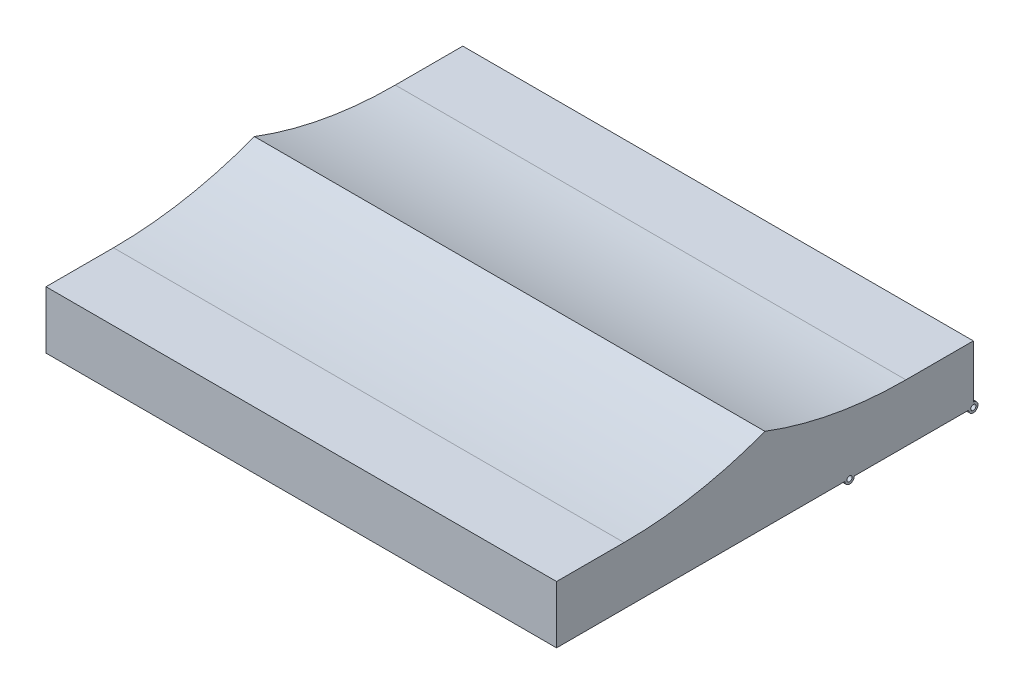
SolidWorks part; units mm, degrees
ref_plane "Plano frontal" through (0, 0, 0) normal (0, 0, 1) x (1, 0, 0)
ref_plane "Plano superior" through (0, 0, 0) normal (0, 1, 0) x (1, 0, 0)
ref_plane "Plano direito" through (0, 0, 0) normal (1, 0, 0) x (0, 0, -1)
sketch "Esboço1" plane through (0, 0, 0) normal (1, 0, 0) x (0, 0, -1)
  line L1 (-200, -19.346) -> (-200, 35.8358)
  line L2 (0, -19.5242) -> (0, 60.6658) construction
  line L3 (-200, 35.8358) -> (-135.24, 35.8358)
  line L5 (200, 35.8358) -> (135.24, 35.8358)
  line L7 (186.5001, -19.5002) -> (195.524, -19.5002)
  line L10 (-200, -19.346) -> (76.73, -19.346)
  line L12 (200, -15.0242) -> (200, 35.8358)
  line L13 (85.73, -19.3548) -> (186.5001, -19.5002)
  circle A1 centre (81.23, -19.346) radius 2.5
  arc A2 (-135.24, 35.8358) -> (0, 60.6658) centre (-135.24, 416.5524) ccw
  arc A3 (135.24, 35.8358) -> (0, 60.6658) centre (135.24, 416.5524) cw
  arc A6 (76.73, -19.346) -> (85.73, -19.3548) centre (81.23, -19.346) ccw
  circle A7 centre (200, -19.5002) radius 2.5
  arc A8 (195.524, -19.5002) -> (200, -15.0242) centre (200, -19.5002) ccw
  point P3 (0, -19.5242)
  dimension "D2" = 118.77
  dimension "D3" = 2
  dimension "D4" = 5
  dimension "D1" = 5
extrude "Ressalto-extrusão1" add sketch "Esboço1" along normal mid plane 490
